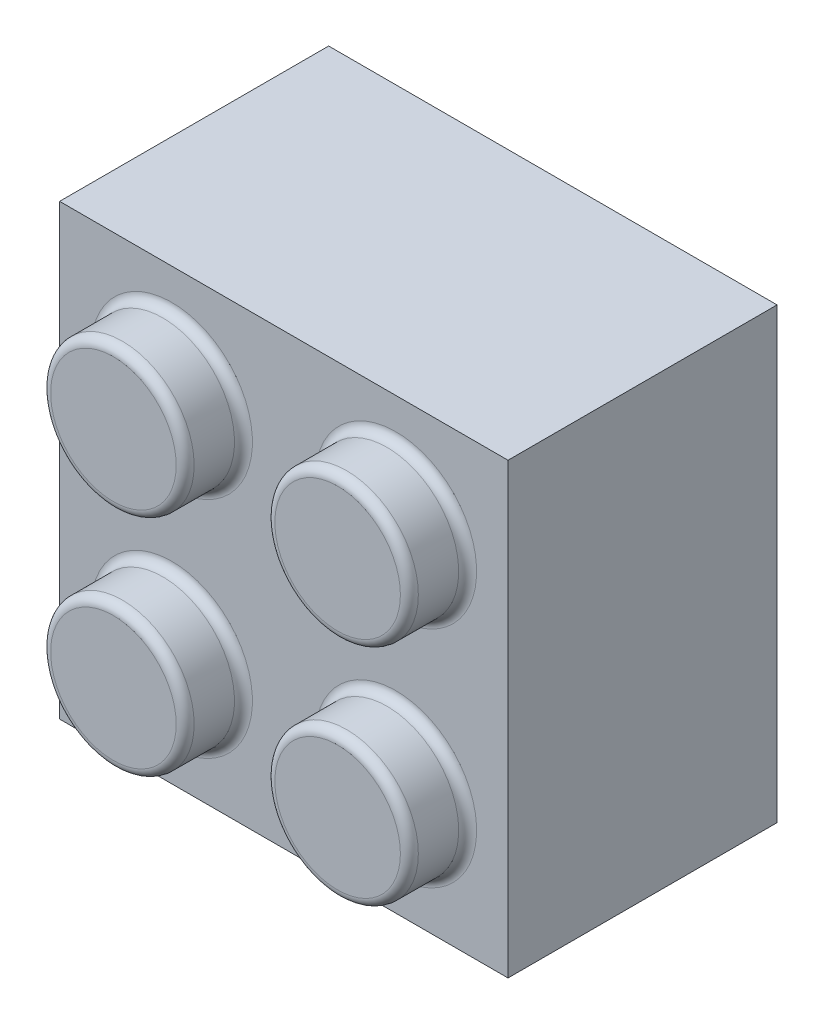
SolidWorks part; units mm, degrees
ref_plane "Plan de face" through (0, 0, 0) normal (0, 0, 1) x (1, 0, 0)
ref_plane "Plan de dessus" through (0, 0, 0) normal (0, 1, 0) x (1, 0, 0)
ref_plane "Plan de droite" through (0, 0, 0) normal (1, 0, 0) x (0, 0, -1)
sketch "Esquisse1" plane through (0, 0, 0) normal (0, 0, 1) x (1, 0, 0)
  line L0 (0, 106.3014) -> (0, -106.3014) construction
  line L1 (101.0831, 0) -> (-105.1308, 0) construction
  line L2 (-50, 50) -> (50, 50)
  line L3 (50, 50) -> (50, -50)
  line L4 (50, -50) -> (-50, -50)
  line L5 (-50, -50) -> (-50, 50)
  point P5 (0, 0)
  point P8 (0, 0)
  point P9 (117.0604, 117.0604)
  point P12 (19.9321, 19.9321)
  point P13 (84.8005, 84.8005)
  point P14 (-55.6422, 55.6422)
  point P15 (55.8539, 55.8539)
  point P16 (0, 0)
  point P17 (-50, 49.0325)
  point P18 (-50, 49.0325)
  point P19 (0, -106.3014)
  dimension "D1" = 100
extrude "Boss.-Extru.2" add sketch "Esquisse1" along normal blind 60 contours L5 L2 L3 L4
sketch "Esquisse2" plane through (0, 0, 60) normal (0, 0, 1) x (1, 0, 0)
  line L0 (0, 50) -> (0, -50) construction
  line L1 (-50, 50) -> (50, 50) construction
  line L2 (50, -50) -> (-50, -50) construction
  line L3 (-50, 0) -> (50, 0) construction
  line L4 (-50, -50) -> (-50, 50) construction
  line L5 (50, 50) -> (50, -50) construction
  line L6 (50, 50) -> (0, 0) construction
  circle A0 centre (25, 25) radius 16
  circle A1 centre (-25, 25) radius 16
  circle A2 centre (-25, -25) radius 16
  circle A3 centre (25, -25) radius 16
  point P20 (0, 0)
  point P23 (0, 0)
  dimension "D1" = 32
extrude "Boss.-Extru.3" add sketch "Esquisse2" along normal blind 13 contours A0 | A2 | A3 | A1
sketch "Esquisse3" plane through (0, 0, 0) normal (0, 0, -1) x (-1, 0, 0)
  line L0 (0, 50) -> (0, -50) construction
  line L1 (50, 50) -> (-50, 50) construction
  line L2 (-50, -50) -> (50, -50) construction
  line L3 (-50, 0) -> (50, 0) construction
  line L4 (-50, 50) -> (-50, -50) construction
  line L5 (50, -50) -> (50, 50) construction
  line L6 (-42, 42) -> (42, 42)
  line L7 (42, 42) -> (42, -42)
  line L8 (42, -42) -> (-42, -42)
  line L9 (-42, -42) -> (-42, 42)
  circle A0 centre (0, 0) radius 12
  circle A1 centre (0, 0) radius 18.5
  dimension "D2" = 24
  dimension "D3" = 37
  dimension "D1" = 8
extrude "Enlèv. mat.-Extru.1" cut sketch "Esquisse3" against normal blind 50 contours L9 L8 L7 L6 A1 | A0
fillet "Congé1" radius 2 8 edges at (-9, -25, 73) (-9, 25, 73) (9, -25, 60) (41, -25, 73) (-41, -25, 60) (9, 25, 60) (41, 25, 73) (-41, 25, 60)
fillet "Congé2" radius 2 3 edges at (-12, 0, 0) (-18.5, 0, 0) (-18.5, 0, 50)
